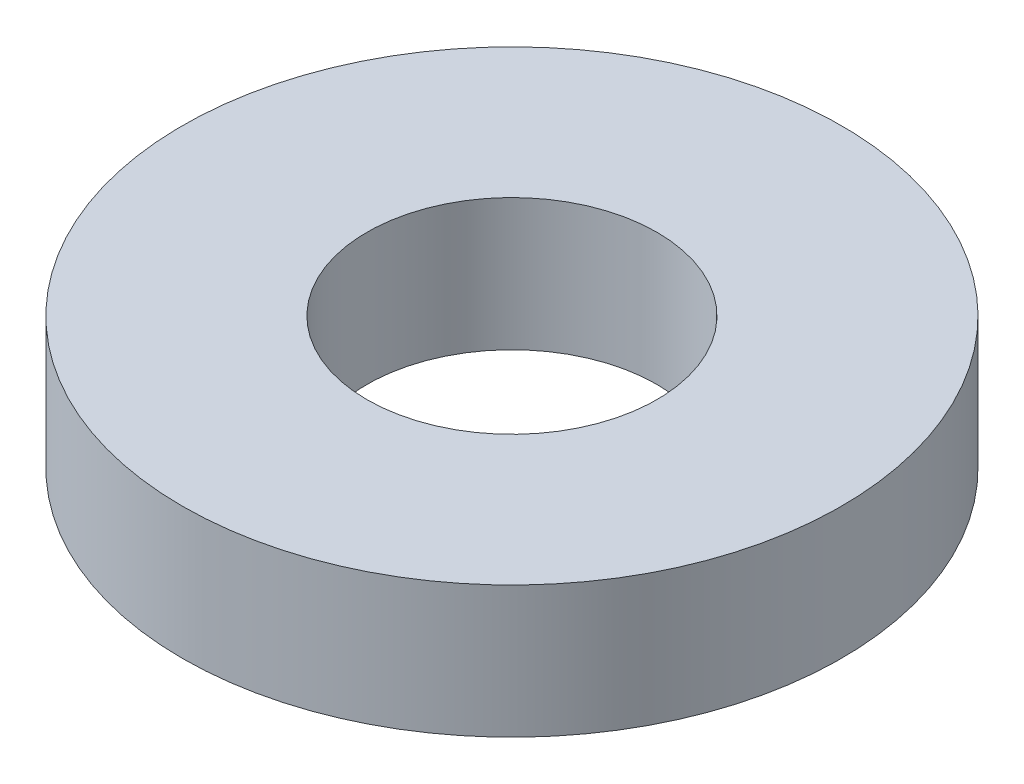
SolidWorks part; units mm, degrees
material "Delrin 2700 NC010, Low Viscosity Acetal Copolymer (SS)"
ref_plane "Front" through (0, 0, 0) normal (0, 0, 1) x (1, 0, 0)
ref_plane "Top" through (0, 0, 0) normal (0, 1, 0) x (1, 0, 0)
ref_plane "Right" through (0, 0, 0) normal (1, 0, 0) x (0, 0, -1)
sketch "Sketch1" plane through (0, 0, 0) normal (0, 1, 0) x (1, 0, 0)
  circle A0 centre (0, 0) radius 1.1
  circle A1 centre (0, 0) radius 2.5
  dimension "D1" = 2.2
  dimension "D2" = 5
extrude "Boss-Extrude1" add sketch "Sketch1" along normal blind 1
